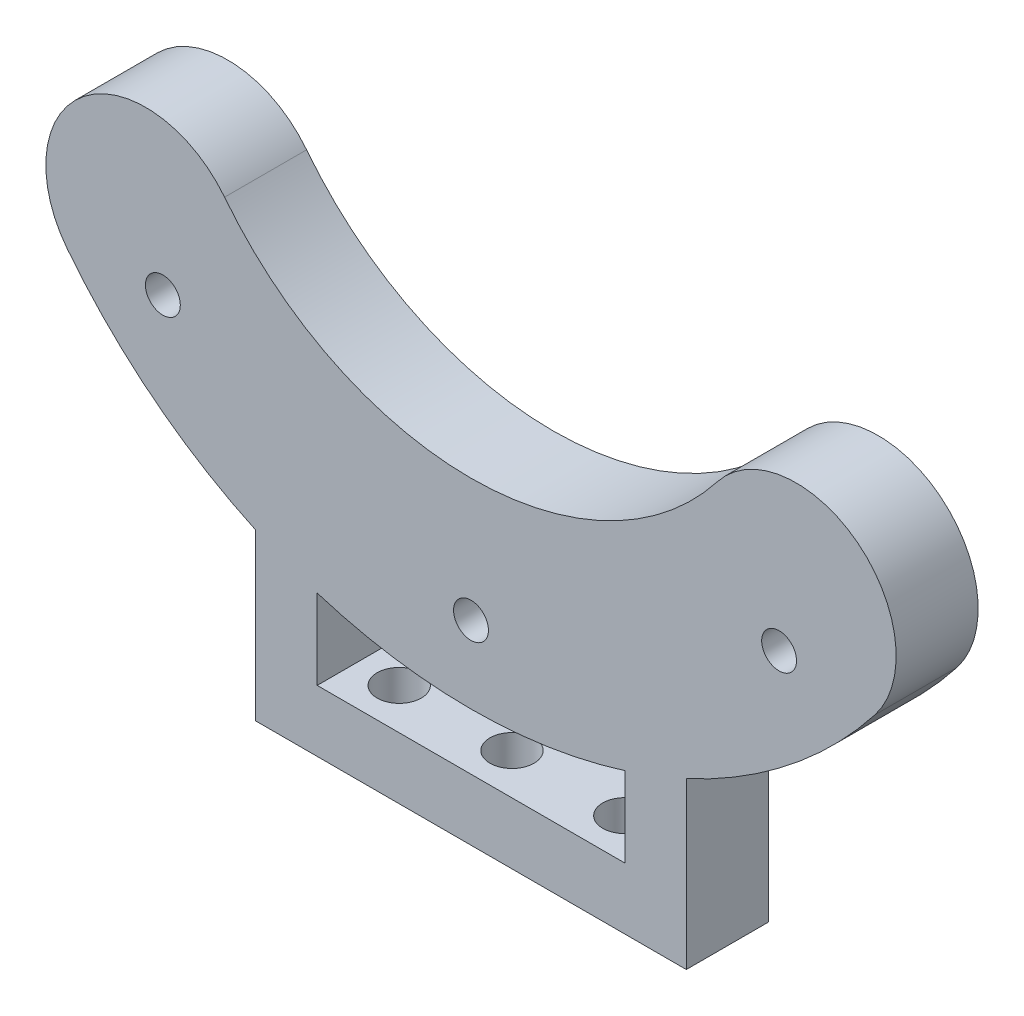
SolidWorks part; units mm, degrees
ref_plane "前视基准面" through (0, 0, 0) normal (0, 0, 1) x (1, 0, 0)
ref_plane "上视基准面" through (0, 0, 0) normal (0, 1, 0) x (1, 0, 0)
ref_plane "右视基准面" through (0, 0, 0) normal (1, 0, 0) x (0, 0, -1)
other "Configuration Table"
sketch "草图1" plane through (0, 0, 0) normal (0, 0, 1) x (1, 0, 0)
  circle A0 centre (0, 0) radius 50
  circle A1 centre (0, 0) radius 42.5 construction
  circle A2 centre (0, 42.5) radius 1.7
  circle A3 centre (30.052, 30.052) radius 1.7
  circle A4 centre (42.5, 0) radius 1.7
  circle A5 centre (30.052, -30.052) radius 1.7
  circle A6 centre (0, -42.5) radius 1.7
  circle A7 centre (-30.052, -30.052) radius 1.7
  circle A8 centre (-42.5, 0) radius 1.7
  circle A9 centre (-30.052, 30.052) radius 1.7
  point P22 (0, 0)
  dimension "D1" = 100
  dimension "D2" = 85
  dimension "D3" = 3.4
  dimension "D4" = 8
extrude "凸台-拉伸1" add sketch "草图1" along normal blind 8
sketch "草图2" plane through (0, 0, 8) normal (0, 0, 1) x (1, 0, 0)
  circle A0 centre (0, 0) radius 30.5
  dimension "D1" = 61
extrude "切除-拉伸1" cut sketch "草图2" against normal blind 8
sketch "草图3" plane through (0, 0, 8) normal (0, 0, 1) x (1, 0, 0)
  line L0 (-50, 0) -> (50, 0) construction
  line L1 (0, 50) -> (0, -50) construction
  line L2 (0, 0) -> (-39.4005, 30.7831) construction
  circle A0 centre (-31.7174, 24.7804) radius 9.75
  circle A1 centre (0, 0) radius 30.5 construction
  circle A2 centre (0, 0) radius 30.5
  circle A3 centre (0, 0) radius 50 construction
  circle A4 centre (0, 0) radius 50
  circle A5 centre (-31.7174, -24.7804) radius 9.75
  circle A6 centre (31.7174, -24.7804) radius 9.75
  circle A7 centre (31.7174, 24.7804) radius 9.75
  circle M7 centre (0, 0) radius 30.5
  circle M8 centre (-42.5, 0) radius 1.7
  circle M10 centre (42.5, 0) radius 1.7
  circle M11 centre (0, 42.5) radius 1.7
  circle M12 centre (0, 0) radius 50
  circle M13 centre (30.052, 30.052) radius 1.7
  circle M16 centre (-30.052, 30.052) radius 1.7
  dimension "D1" = 38
extrude "切除-拉伸6" cut sketch "草图3" against normal blind 84 contours A7 A2 A6 M12 M10 | A7 A4 A0 M7 M11 | A5 A2 A0 M12 M8 | A0 M16 | A7 M13
sketch "草图8" plane through (0, 0, 8) normal (0, 0, 1) x (1, 0, 0)
  line L0 (-21, -45.3762) -> (-21, -61.5)
  line L1 (0, -30.5) -> (0, -50) construction
  line L2 (21, -45.3762) -> (21, -61.5)
  line L3 (-21, -61.5) -> (21, -61.5)
  line L4 (-15, -45.3762) -> (-15, -55.5)
  line L5 (-15, -55.5) -> (15, -55.5)
  line L6 (15, -45.3762) -> (15, -55.5)
  arc A4 (-39.4005, -30.7831) -> (39.4005, -30.7831) centre (0, 0) ccw
  arc A5 (39.4005, -30.7831) -> (24.0343, -18.7777) centre (31.7174, -24.7804) ccw
  arc A6 (-24.0343, -18.7777) -> (24.0343, -18.7777) centre (0, 0) ccw
  arc A7 (-24.0343, -18.7777) -> (-39.4005, -30.7831) centre (-31.7174, -24.7804) ccw
  arc A8 (-39.4005, -30.7831) -> (39.4005, -30.7831) centre (0, 0) ccw
  arc A9 (39.4005, -30.7831) -> (24.0343, -18.7777) centre (31.7174, -24.7804) ccw
  arc A10 (-24.0343, -18.7777) -> (24.0343, -18.7777) centre (0, 0) ccw
  arc A11 (-24.0343, -18.7777) -> (-39.4005, -30.7831) centre (-31.7174, -24.7804) ccw
  arc M12 (-39.4005, -30.7831) -> (39.4005, -30.7831) centre (0, 0) ccw
  dimension "D2" = 42
  dimension "D3" = 11.5
  dimension "D1" = 0
  dimension "D4" = 6
extrude "凸台-拉伸5" add sketch "草图8" against normal blind 8 contours L6 L5 L4 L0 L3 L2 M12
sketch "草图10" plane through (0, -61.5, 0) normal (0, -1, 0) x (1, 0, 0)
  line L0 (-21, 4) -> (21, 4) construction
  line L1 (0, 8) -> (0, 0) construction
  line L4 (21, 8) -> (-21, 8)
  line L5 (-21, 8) -> (-21, 0)
  line L6 (-21, 0) -> (21, 0)
  line L7 (21, 0) -> (21, 8)
  line L8 (21, 8) -> (-21, 8)
  line L9 (-21, 8) -> (-21, 0)
  line L10 (-21, 0) -> (21, 0)
  line L11 (21, 0) -> (21, 8)
  circle A0 centre (-11, 4) radius 2.15
  circle A1 centre (0, 4) radius 2.15
  circle A2 centre (11, 4) radius 2.15
  dimension "D2" = 4.3
  dimension "D3" = 4.3
  dimension "D4" = 10
  dimension "D1" = 0
extrude "切除-拉伸7" cut sketch "草图10" against normal blind 8 contours A0 | A1 | A2
